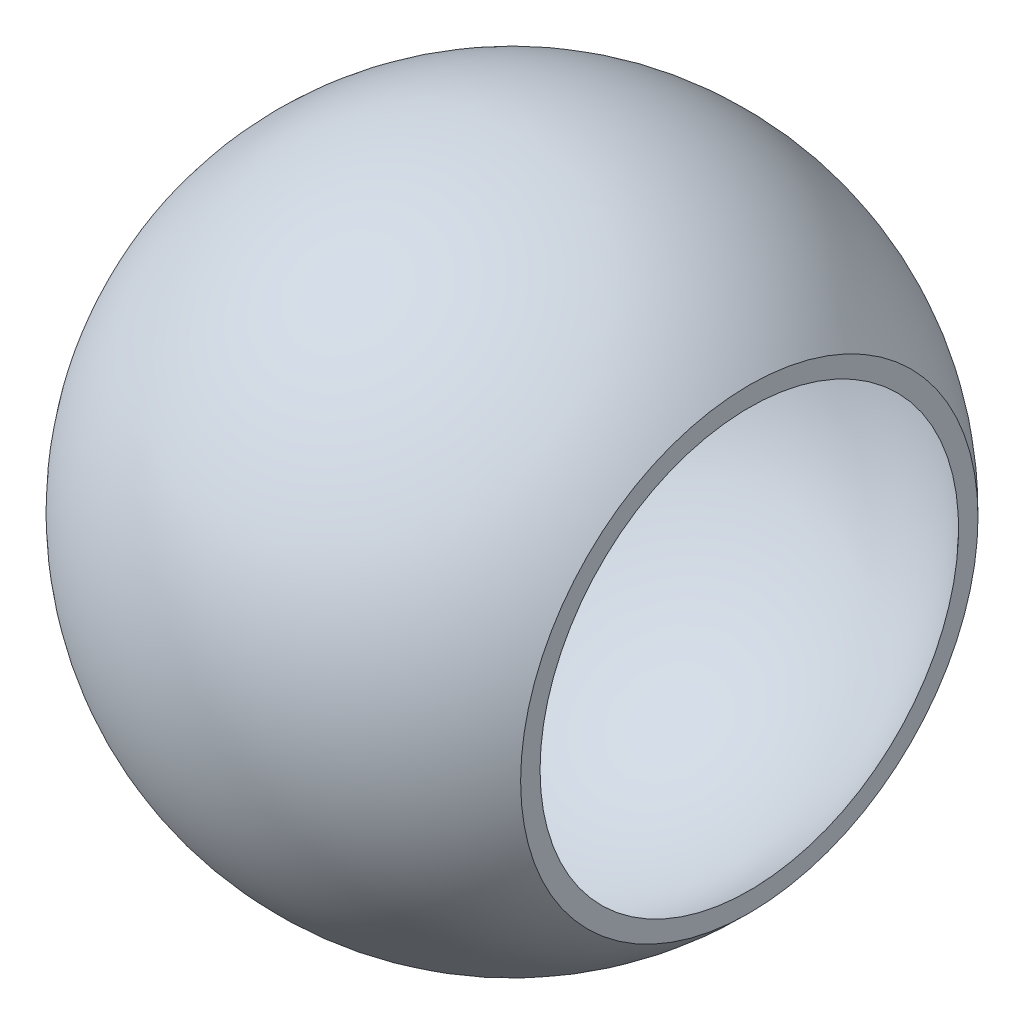
SolidWorks part; units mm, degrees
ref_plane "Front Plane" through (0, 0, 0) normal (0, 0, 1) x (1, 0, 0)
ref_plane "Top Plane" through (0, 0, 0) normal (0, 1, 0) x (1, 0, 0)
ref_plane "Right Plane" through (0, 0, 0) normal (1, 0, 0) x (0, 0, -1)
sketch "Sketch1" plane through (0, 0, 0) normal (0, 0, 1) x (1, 0, 0)
  line L0 (-63.5, 0) -> (-60.96, 0)
  line L2 (45.72, 44.0674) -> (45.72, 40.3212)
  line L5 (0, -55) -> (0, 55) construction
  arc A0 (45.72, 44.0674) -> (-63.5, 0) centre (0, 0) ccw
  arc A1 (45.72, 40.3212) -> (-60.96, 0) centre (0, 0) ccw
  dimension "D1" = 63.5
  dimension "D2" = 60.96
  dimension "D3" = 45.72
revolve "Revolve1" add sketch "Sketch1" angle 360 about L0
sketch "Sketch2" plane through (0, 0, 0) normal (1, 0, 0) x (0, 0, -1)
  line L0 (0, 69.85) -> (0, -69.85) construction
  line L1 (69.85, 0) -> (-69.85, 0) construction
  circle A0 centre (0, 10.0076) radius 21.59
  circle A1 centre (0, 10.0076) radius 17.145
  dimension "D1" = 10.0076
  dimension "D2" = 34.29
  dimension "D3" = 43.18
extrude "Boss-Extrude1" add sketch "Sketch2" against normal up to next from offset 38.1 offset against normal yes
